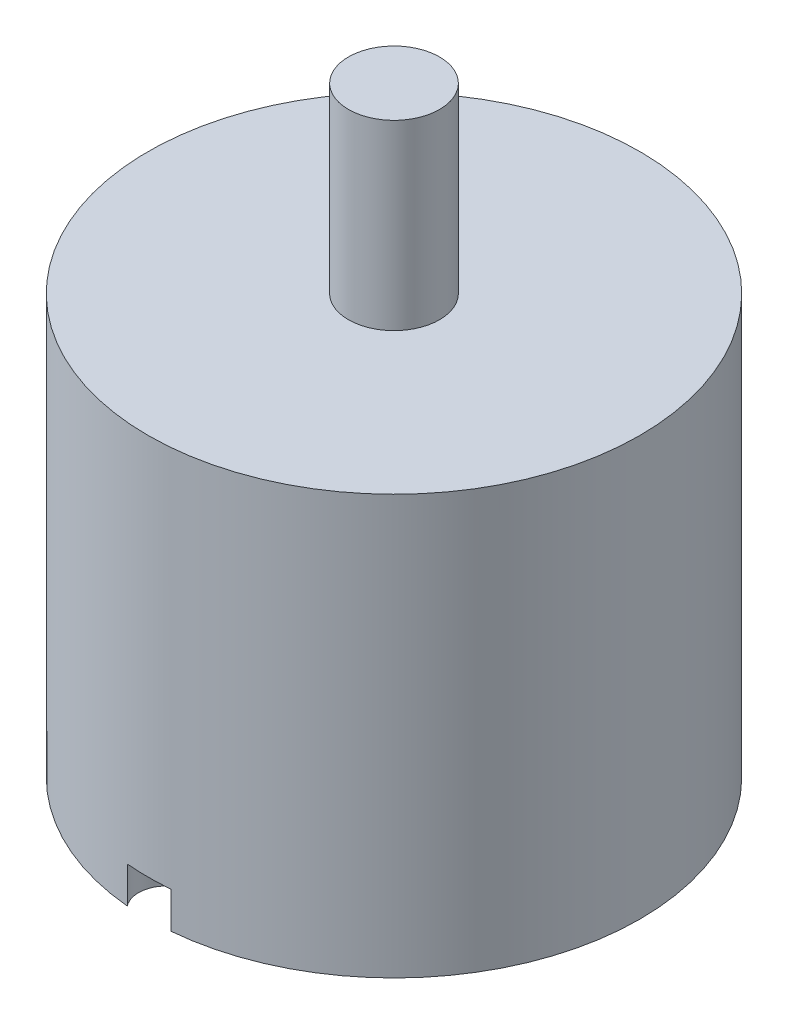
SolidWorks part; units mm, degrees
ref_plane "Front Plane" through (0, 0, 0) normal (0, 0, 1) x (1, 0, 0)
ref_plane "Top Plane" through (0, 0, 0) normal (0, 1, 0) x (1, 0, 0)
ref_plane "Right Plane" through (0, 0, 0) normal (1, 0, 0) x (0, 0, -1)
sketch "Sketch1" plane through (0, 0, 0) normal (0, 1, 0) x (1, 0, 0)
  circle A0 centre (0, 0) radius 13.5
  dimension "D1" = 26.9999
extrude "Boss-Extrude1" add sketch "Sketch1" along normal blind 23
sketch "Sketch2" plane through (0, 23, 0) normal (0, 1, 0) x (1, 0, 0)
  circle A0 centre (0, 0) radius 2.5
  dimension "D1" = 5
extrude "Boss-Extrude2" add sketch "Sketch2" along normal blind 10
sketch "Sketch3" plane through (0, 0, 0) normal (0, -1, 0) x (1, 0, 0)
  circle A0 centre (0, 0) radius 1.5
  dimension "D1" = 3
extrude "Boss-Extrude3" add sketch "Sketch3" along normal blind 2
sketch "Sketch4" plane through (0, 0, 0) normal (0, -1, 0) x (1, 0, 0)
  line L0 (0, 0) -> (0, 8.6454) construction
  line L1 (0, 0) -> (7.4808, 0) construction
  circle A0 centre (0, 12.5) radius 1.524
  circle A1 centre (9.5, 0) radius 1.5
  circle A2 centre (-9.5, 0) radius 1.5
  circle A3 centre (0, -12.5) radius 1.524
  dimension "D1" = 3.048
  dimension "D2" = 3
  dimension "D3" = 9.5
  dimension "D4" = 12.5
extrude "Cut-Extrude1" cut sketch "Sketch4" against normal blind 2
equation "\"Motor Y\"= \"Motor Screw Y@Quad Assemb.sldasm\""
equation "\"D4@Sketch4\"=\"Motor Y\"/2"
equation "\"Motor X\"= \"Motor Screw X@Quad Assemb.sldasm\""
equation "\"D3@Sketch4\"=\"Motor X\"/2"
equation "\"Motor Diam\"= \"Motor Diam@Quad Assemb.sldasm\""
equation "\"D1@Sketch1\"=\"Motor Diam\""
equation "\"D1@Boss-Extrude1\"=\"Motor Length@Quad Assemb.sldasm\""
equation "\"D1@Sketch3\"=\"motor shaft diam@quad assemb.sldasm\""
